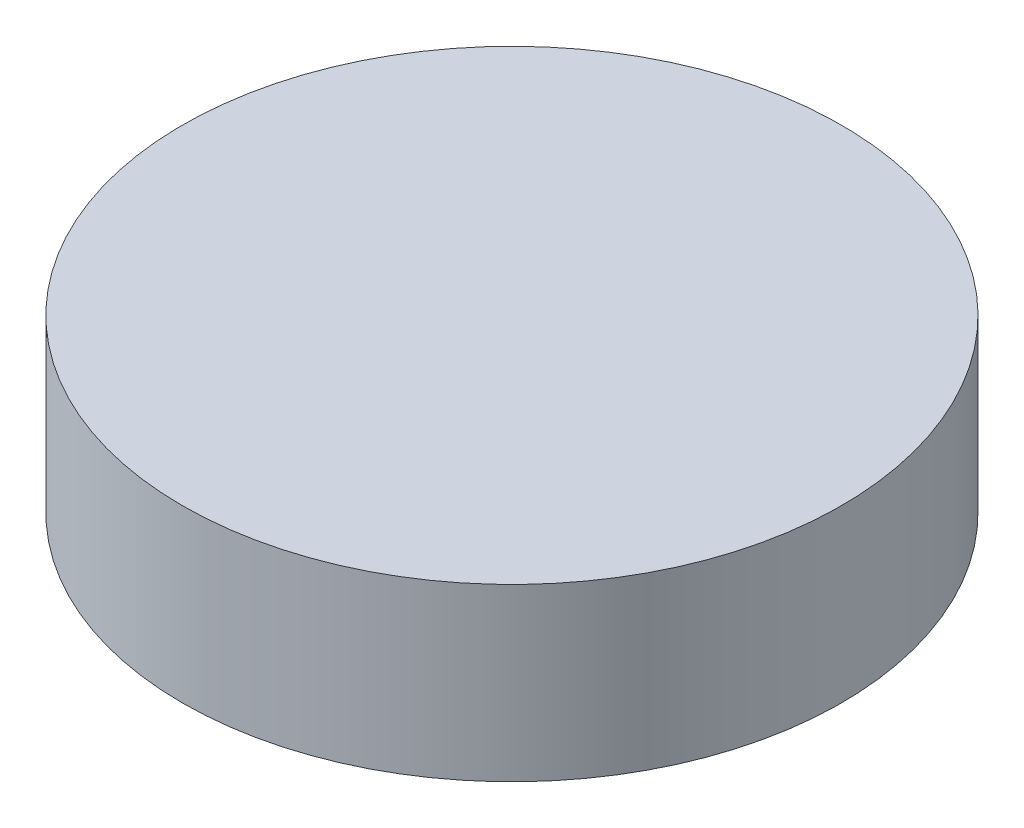
SolidWorks part; units mm, degrees
ref_plane "Plano frontal" through (0, 0, 0) normal (0, 0, 1) x (1, 0, 0)
ref_plane "Plano superior" through (0, 0, 0) normal (0, 1, 0) x (1, 0, 0)
ref_plane "Plano direito" through (0, 0, 0) normal (1, 0, 0) x (0, 0, -1)
sketch "Esboço1" plane through (0, 0, 0) normal (0, 1, 0) x (1, 0, 0)
  circle A0 centre (0, 0) radius 13.5
  dimension "D1" = 27
extrude "Ressalto-extrusão1" add sketch "Esboço1" along normal blind 7
